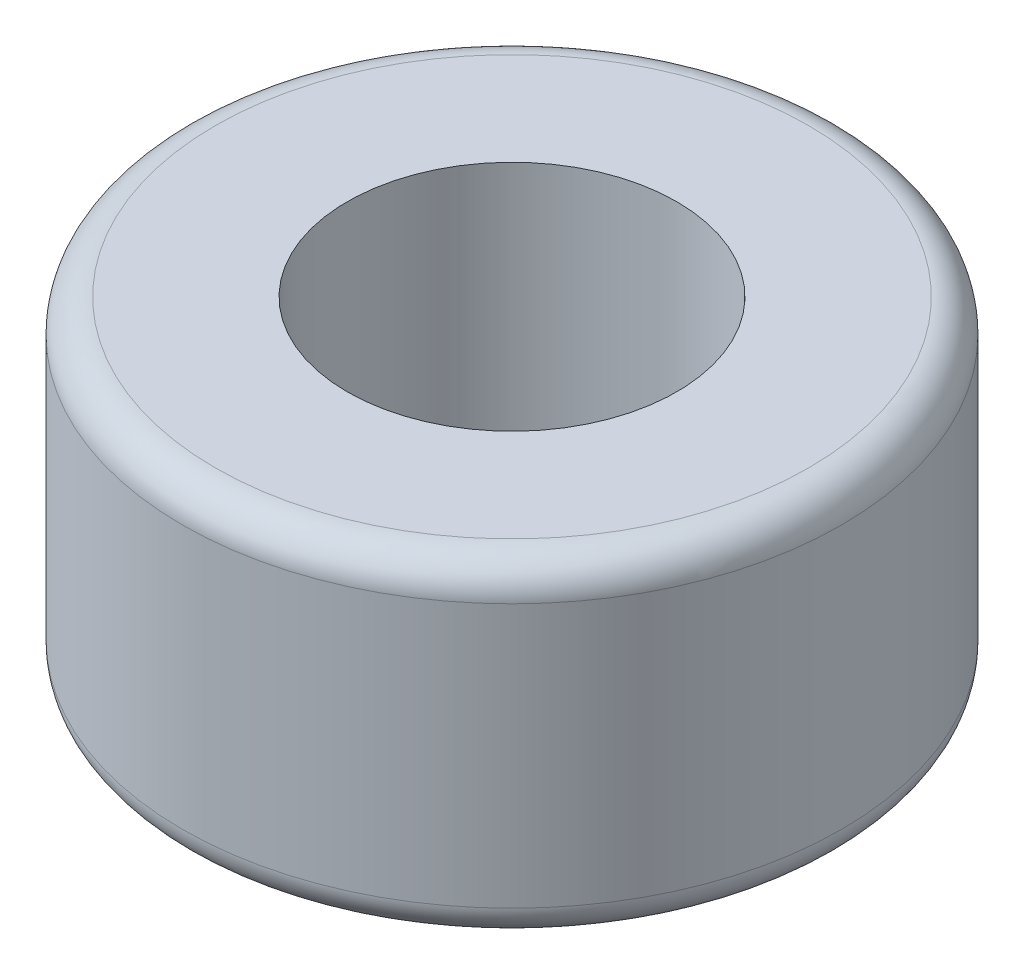
SolidWorks part; units mm, degrees
ref_plane "Front Plane" through (0, 0, 0) normal (0, 0, 1) x (1, 0, 0)
ref_plane "Top Plane" through (0, 0, 0) normal (0, 1, 0) x (1, 0, 0)
ref_plane "Right Plane" through (0, 0, 0) normal (1, 0, 0) x (0, 0, -1)
sketch "Sketch1" plane through (0, 0, 0) normal (0, 1, 0) x (1, 0, 0)
  circle A0 centre (0, 0) radius 0.5
  circle A1 centre (0, 0) radius 1
  dimension "D1" = 1
  dimension "D2" = 0.5
extrude "Boss-Extrude1" add sketch "Sketch1" along normal blind 1
fillet "Fillet1" radius 0.1 1 edges at (0, 1, 1)
fillet "Fillet2" radius 0.1 1 edges at (0, 0, 1)
